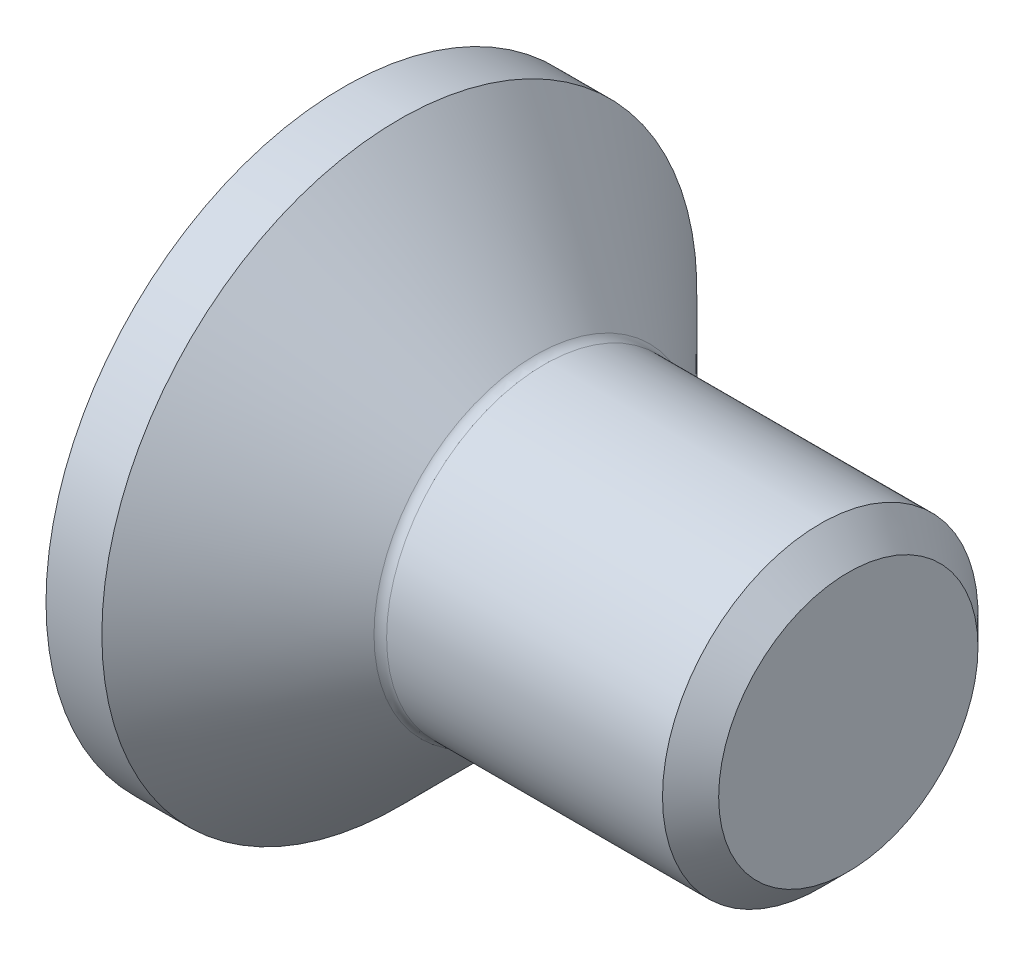
SolidWorks part; units mm, degrees
ref_plane "Plane1" through (0, 0, 0) normal (0, 0, 1) x (1, 0, 0)
ref_plane "Plane2" through (0, 0, 0) normal (0, 1, 0) x (1, 0, 0)
ref_plane "Plane3" through (0, 0, 0) normal (1, 0, 0) x (0, 0, -1)
sketch "BodySke" plane through (0, 0, 0) normal (0, 0, 1) x (1, 0, 0)
  line L0 (0, 0) -> (0, 4.715)
  line L1 (0.885, 4.715) -> (3.1, 2.5)
  line L2 (0, 4.715) -> (0.885, 4.715)
  line L3 (3.1, 2.5) -> (7.555, 2.5)
  line L4 (8, 2.055) -> (8, 0)
  line L5 (8, 0) -> (0, 0)
  line L6 (0, 0) -> (127, 0) construction
  line L7 (0.885, -4.715) -> (3.1, -2.5) construction
  line L8 (8, 2.055) -> (7.555, 2.5)
  line L9 (0, -4.715) -> (0.885, -4.715) construction
  line L10 (8, -2.055) -> (7.555, -2.5) construction
  line L11 (3.9, 8.85) -> (3.9, -13.375) construction
  line L12 (0, 19.05) -> (0, -3.175) construction
  dimension "D1" = 0.885
  dimension "Diameter" = 5
  dimension "Head_ht" = 3.1
  dimension "Length" = 8
  dimension "Body_ch_ang" = 45
  dimension "Head_dia" = 9.43
  dimension "Minor_dia" = 4.11
  dimension "Head_ang" = 90
  dimension "Advance" = 0.8
  dimension "Thread_nom" = 8
revolve "BaseBody" add sketch "BodySke"
cosmetic thread "ThreadCosmetic" [suppressed]
fillet "Fillet1" radius 0.2 1 edges at (3.1, 0, 2.5)
sketch "Sketch2" plane through (0, 0, 0) normal (0, 0, 1) x (1, 0, 0)
  line L0 (0, 1.5) -> (1.9, 1.5)
  line L1 (1.9, 1.5) -> (2.766, 0)
  line L2 (0, 0) -> (127, 0) construction
  line L3 (2.766, 0) -> (0, 0)
  line L4 (0, 0) -> (0, 1.5)
  line L5 (0, -1.5) -> (1.9, -1.5) construction
  line L6 (0, 0) -> (47.625, 0) construction
  line L8 (0, 4.715) -> (0, -4.715) construction
  dimension "D2" = 60
  dimension "PreBroach_depth" = 1.9
  dimension "PreBroach_dia" = 3
revolve "PreBroach" cut sketch "Sketch2" angle 360 about L6
sketch "Sketch3" plane through (0, 0, 0) normal (-1, 0, 0) x (0, 0, 1)
  line L0 (-1.5, -0.866) -> (-1.5, 0.866)
  line L1 (-1.5, 0.866) -> (0, 1.7321)
  line L2 (0, 1.7321) -> (1.5, 0.866)
  line L3 (1.5, 0.866) -> (1.5, -0.866)
  line L4 (1.5, -0.866) -> (0, -1.7321)
  line L5 (0, -1.7321) -> (-1.5, -0.866)
  dimension "D1" = 1.5
  dimension "D2" = 1.5
  dimension "D3" = 3
  dimension "Hex_size" = 3
extrude "Hex" cut sketch "Sketch3" against normal blind 1.9
sketch "ThdSchSke" plane through (0, 0, 0) normal (0, 0, 1) x (1, 0, 0)
  line L0 (5.5, -2.055) -> (5.1884, -2.5)
  line L1 (5.5, -2.055) -> (5.8116, -2.5)
  line L2 (5.8116, -2.5) -> (5.8116, -3.125)
  line L3 (-3.175, 0) -> (5.1513, 0) construction
  line L4 (0, 4.715) -> (0, -4.715) construction
  line L5 (5.8116, -3.125) -> (5.1884, -3.125)
  line L6 (5.1884, -3.125) -> (5.1884, -2.5)
  dimension "Thread_minor" = 4.11
  dimension "Diameter" = 5
  dimension "Start" = 5.5
  dimension "SideAngle" = 55
  dimension "VeeAngle" = 70
  dimension "Overcut" = 6.25
revolve "ThreadSchematic" [suppressed] cut sketch "ThdSchSke" angle 360 about L3
pattern_linear "ThdSchPat" [suppressed]
equation "\"Thread_minor@ThreadCosmetic\"  =  \"Minor_dia@BodySke\""
equation "\"D1@Sketch3\" = \"Hex_size@Sketch3\" / 2"
equation "\"D2@Sketch3\" = \"D1@Sketch3\""
equation "\"D3@Sketch3\" = \"Hex_size@Sketch3\""
equation "\"Thread_length@ThreadCosmetic\" = ((sgn( (\"Length@BodySke\" - \"Advance@BodySke\" * 3.0 - \"Head_ht@BodySke\" ) - \"Thread_nom@BodySke\" )-1)*( (\"Length@BodySke\" - \"Advance@BodySke\" * 3.0 - \"Head_ht@BodySke\" ) - \"Thread_nom@BodySke\" ))/-2+ \"Thread_nom@BodySke\""
equation "\"Thread_minor@ThdSchSke\" = \"Minor_dia@BodySke\""
equation "\"Diameter@ThdSchSke\" = \"Diameter@BodySke\""
equation "\"Overcut@ThdSchSke\" = \"Diameter@BodySke\" * 1.25"
equation "\"Start@ThdSchSke\" = 0.000001 + \"Length@BodySke\" - \"Thread_length@ThreadCosmetic\"  '---Countersunk---"
equation "\"Num_threads@ThdSchPat\" = int( \"Thread_length@ThreadCosmetic\" / \"Advance@BodySke\" + 0.999 )  + 1"
equation "\"Advance@ThdSchPat\" = \"Thread_length@ThreadCosmetic\" /  (\"Num_threads@ThdSchPat\" - 1) 'relax it"
equation "\"Num_threads@ThdSchPat\" = \"Num_threads@ThdSchPat\" - sgn( \"Num_threads@ThdSchPat\" - 1) '---chamfered tips only---"
